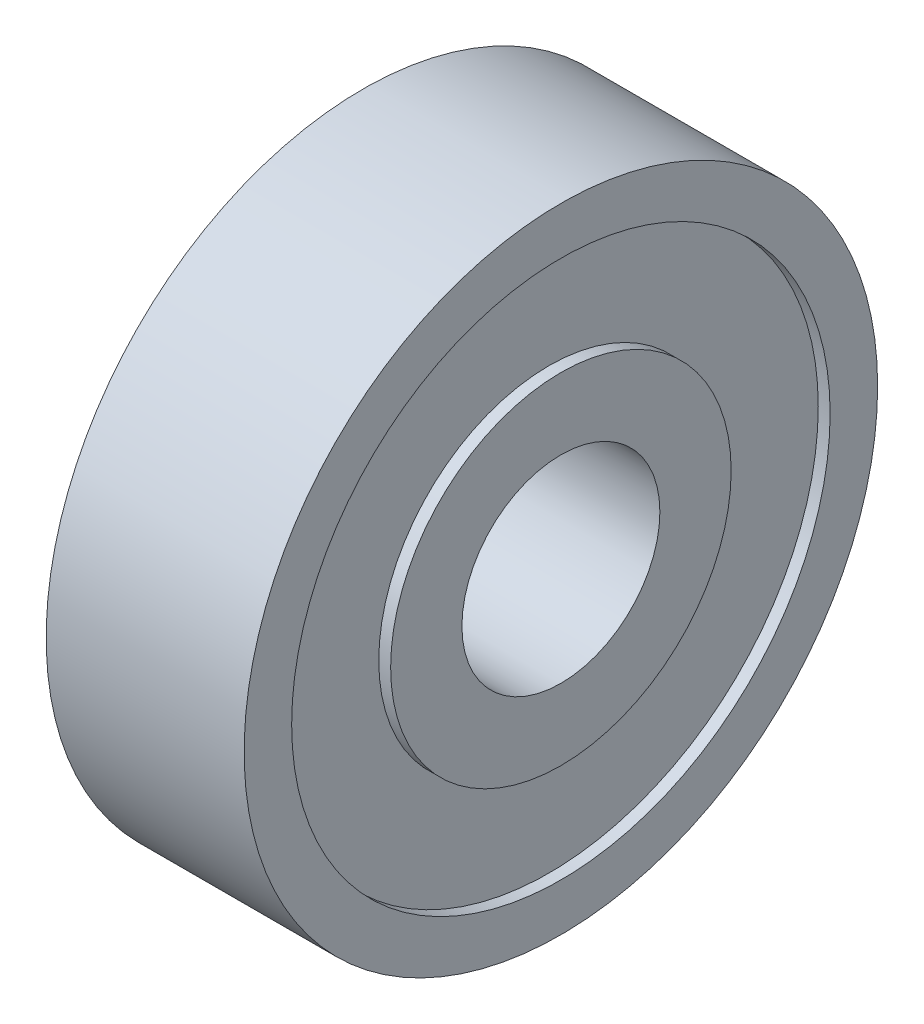
SolidWorks part; units mm, degrees
material "Stainless Steel (ferritic)"
ref_plane "Front Plane" through (0, 0, 0) normal (0, 0, 1) x (1, 0, 0)
ref_plane "Top Plane" through (0, 0, 0) normal (0, 1, 0) x (1, 0, 0)
ref_plane "Right Plane" through (0, 0, 0) normal (1, 0, 0) x (0, 0, -1)
sketch "Sketch1" plane through (0, 0, 0) normal (0, 0, 1) x (1, 0, 0)
  line L0 (-2.5, 4.3) -> (-2.5, 2.5)
  line L1 (-2.5, 2.5) -> (2.5, 2.5)
  line L2 (2.5, 2.5) -> (2.5, 4.3)
  line L3 (2.5, 4.3) -> (2.2, 4.3)
  line L4 (2.2, 4.3) -> (2.2, 6.8)
  line L5 (2.2, 6.8) -> (2.5, 6.8)
  line L6 (2.5, 6.8) -> (2.5, 8)
  line L7 (2.5, 8) -> (-2.5, 8)
  line L8 (-2.5, 8) -> (-2.5, 6.8)
  line L9 (-2.5, 6.8) -> (-2.2, 6.8)
  line L10 (-2.2, 6.8) -> (-2.2, 4.3)
  line L11 (-2.2, 4.3) -> (-2.5, 4.3)
  line L12 (-2.5, 0) -> (2.5, 0) construction
revolve "Revolve1" add sketch "Sketch1" angle 360 about L12
